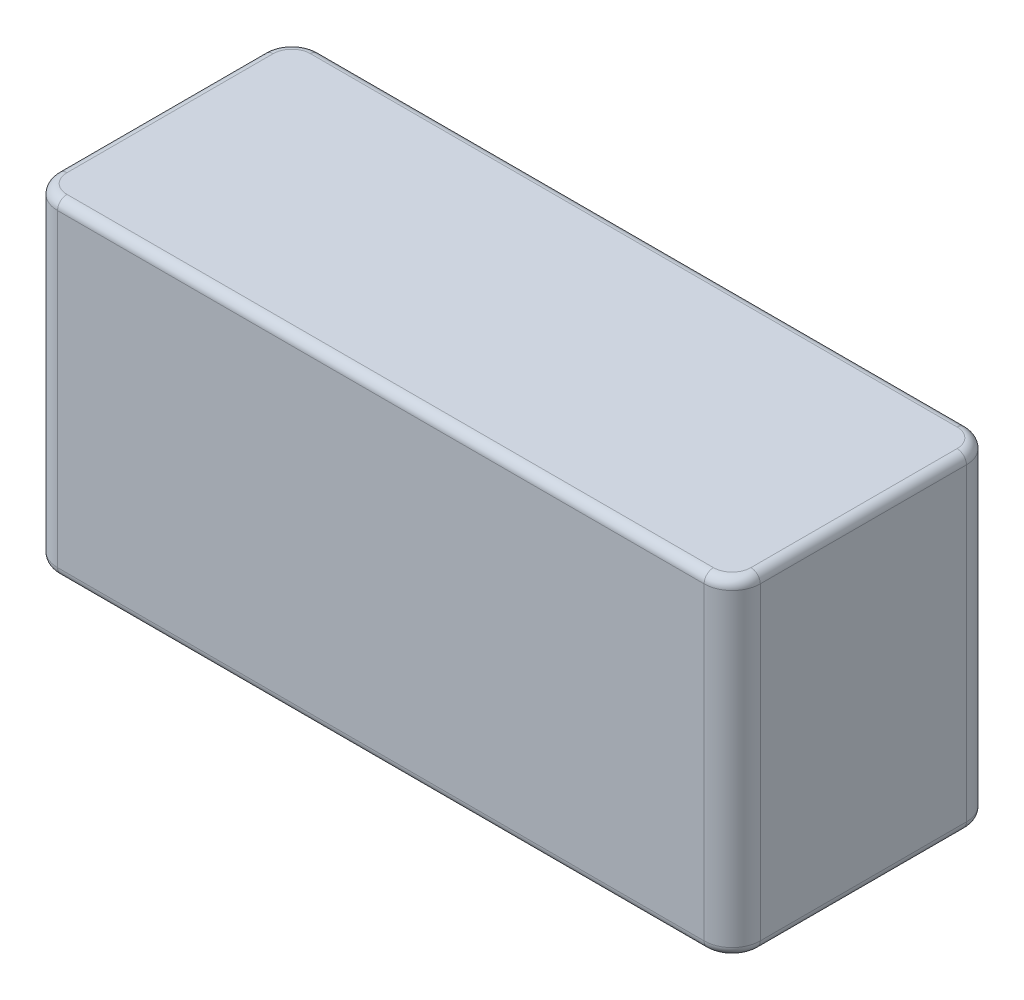
SolidWorks part; units mm, degrees
ref_plane "Front Plane" through (0, 0, 0) normal (0, 0, 1) x (1, 0, 0)
ref_plane "Top Plane" through (0, 0, 0) normal (0, 1, 0) x (1, 0, 0)
ref_plane "Right Plane" through (0, 0, 0) normal (1, 0, 0) x (0, 0, -1)
sketch "Sketch1" plane through (0, 0, 0) normal (0, 1, 0) x (1, 0, 0)
  line L1 (-37.5, -14) -> (37.5, -14)
  line L2 (-37.5, -14) -> (-37.5, 14)
  line L3 (-37.5, 14) -> (37.5, 14)
  line L4 (37.5, -14) -> (37.5, 14)
  line L5 (-37.5, -14) -> (37.5, 14) construction
  line L6 (-37.5, 14) -> (37.5, -14) construction
  point P0 (0, 0)
  dimension "D1" = 75
  dimension "D2" = 28
extrude "Boss-Extrude1" add sketch "Sketch1" along normal blind 35
fillet "Fillet1" radius 3 4 edges at (-37.5, 17.5, 14) (-37.5, 17.5, -14) (37.5, 17.5, -14) (37.5, 17.5, 14)
fillet "Fillet2" radius 1 16 edges at (-36.6213, 35, -13.1213) (0, 35, -14) (36.6213, 35, -13.1213) (37.5, 35, 0) (36.6213, 35, 13.1213) (0, 35, 14) (-36.6213, 35, 13.1213) (-37.5, 35, 0) (36.6213, 0, 13.1213) (37.5, 0, 0) (36.6213, 0, -13.1213) (0, 0, -14) (-36.6213, 0, -13.1213) (-37.5, 0, 0) (-36.6213, 0, 13.1213) (0, 0, 14)
